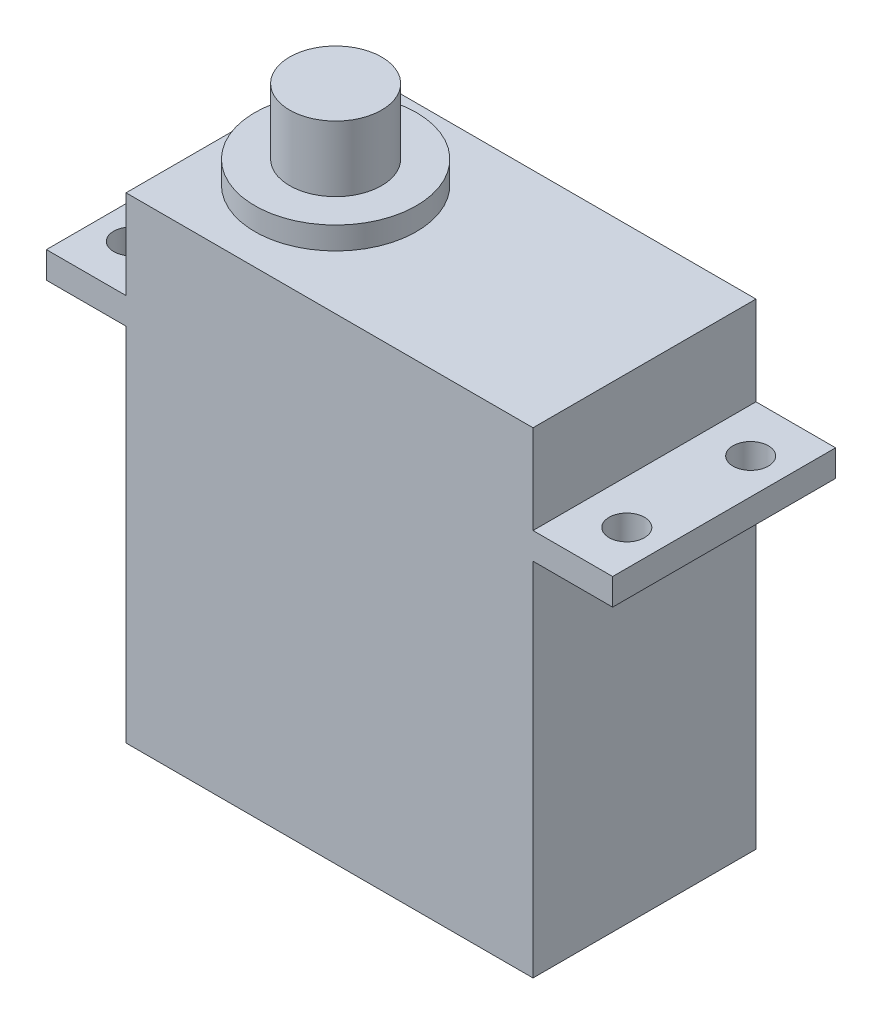
SolidWorks part; units mm, degrees
ref_plane "前视基准面" through (0, 0, 0) normal (0, 0, 1) x (1, 0, 0)
ref_plane "上视基准面" through (0, 0, 0) normal (0, 1, 0) x (1, 0, 0)
ref_plane "右视基准面" through (0, 0, 0) normal (1, 0, 0) x (0, 0, -1)
sketch "草图1" plane through (0, 0, 0) normal (0, 0, 1) x (1, 0, 0)
  line L1 (-11.5, 13.465) -> (11.5, 13.465)
  line L2 (-11.5, 13.465) -> (-11.5, -13.465)
  line L3 (-11.5, -13.465) -> (11.5, -13.465)
  line L4 (11.5, 13.465) -> (11.5, -13.465)
  line L5 (0, -13.465) -> (0, 13.465) construction
  line L6 (-11.5, 0) -> (11.5, 0) construction
  line L7 (-16, 8.435) -> (16, 8.435)
  line L8 (-16, 8.435) -> (-16, 6.935)
  line L9 (-16, 6.935) -> (16, 6.935)
  line L10 (16, 8.435) -> (16, 6.935)
  line L11 (0, 6.935) -> (0, 8.435) construction
  line L12 (-16, 7.685) -> (16, 7.685) construction
  point P0 (0, 0)
  point P4 (0, 7.685)
  dimension "D1" = 23
  dimension "D2" = 26.93
  dimension "D3" = 1.5
  dimension "D4" = 32
  dimension "D5" = 20.4
extrude "凸台-拉伸1" add sketch "草图1" along normal mid plane 12.6 from offset 0 contours L2 L7 L4 L1 | L10 L7 L4 L9 | L9 L2 L3 L4 | L8 L9 L2 L7 | L2 L9 L4 L7
sketch "草图2" plane through (0, 0, 0) normal (0, 0, 1) x (1, 0, 0)
  line L0 (-5.955, 10.8397) -> (-5.955, 21.1803) construction
  line L1 (-5.955, 13.465) -> (-10.52, 13.465)
  line L2 (-11.5, 13.465) -> (11.5, 13.465) construction
  line L3 (-10.52, 13.465) -> (-10.52, 14.735)
  line L4 (-10.52, 14.735) -> (-8.555, 14.735)
  line L5 (-8.555, 14.735) -> (-8.555, 18.435)
  line L6 (-8.555, 18.435) -> (-5.955, 18.435)
  line L7 (-16, 8.435) -> (-11.5, 8.435) construction
  line L8 (-11.5, 13.465) -> (-11.5, 8.435) construction
  line L9 (-5.955, 13.465) -> (-5.955, 18.435)
  dimension "D1" = 6.3
  dimension "D2" = 3.7
  dimension "D3" = 5.545
  dimension "D4" = 5.2
  dimension "D5" = 9.13
revolve "旋转1" add sketch "草图2" angle 360 about L0
sketch "草图3" plane through (0, 8.435, 0) normal (0, 1, 0) x (1, 0, 0)
  line L0 (-16, 0) -> (16, 0) construction
  line L1 (-16, -6.3) -> (-16, 6.3) construction
  line L2 (16, -6.3) -> (16, 6.3) construction
  line L3 (0, 0) -> (0, -9.6648) construction
  circle A0 centre (-14, 3.5) radius 1
  circle A1 centre (14, 3.5) radius 1
  circle A2 centre (14, -3.5) radius 1
  circle A3 centre (-14, -3.5) radius 1
  dimension "D1" = 2
  dimension "D2" = 2
  dimension "D3" = 7
  dimension "D4" = 7
  dimension "D5" = 28
  dimension "D6" = 28
extrude "切除-拉伸1" cut sketch "草图3" against normal blind 10
